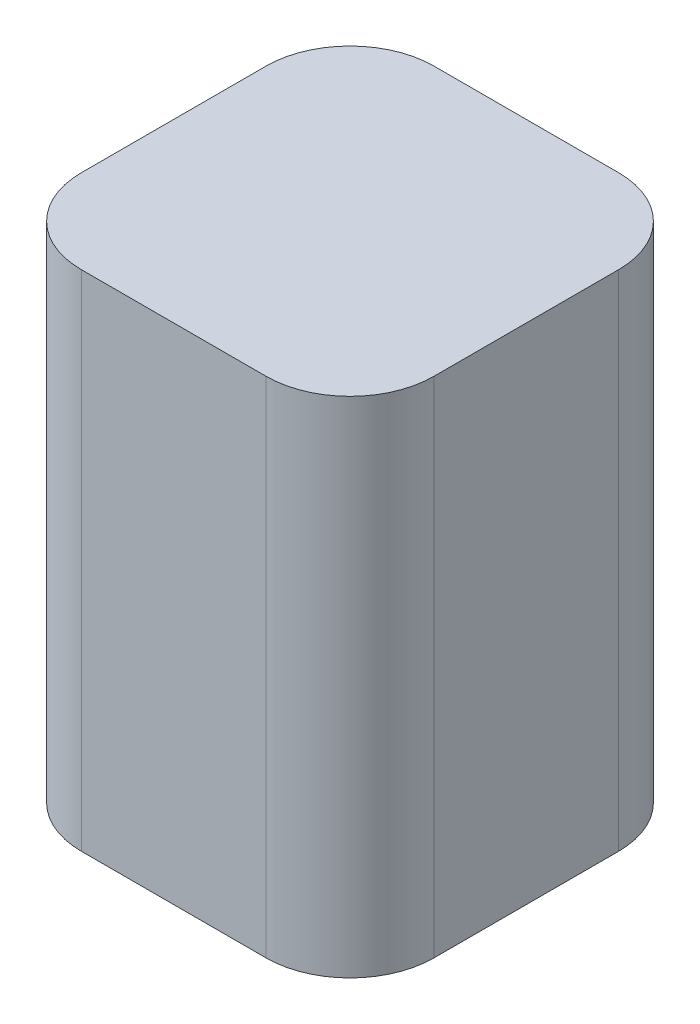
SolidWorks part; units mm, degrees
ref_plane "Front Plane" through (0, 0, 0) normal (0, 0, 1) x (1, 0, 0)
ref_plane "Top Plane" through (0, 0, 0) normal (0, 1, 0) x (1, 0, 0)
ref_plane "Right Plane" through (0, 0, 0) normal (1, 0, 0) x (0, 0, -1)
sketch "Sketch1" plane through (0, 0, 0) normal (0, 1, 0) x (1, 0, 0)
  line L1 (-21, 21) -> (21, 21)
  line L2 (-21, 21) -> (-21, -21)
  line L3 (-21, -21) -> (21, -21)
  line L4 (21, 21) -> (21, -21)
  line L5 (-21, 21) -> (21, -21) construction
  line L6 (-21, -21) -> (21, 21) construction
  point P0 (0, 0)
  dimension "D1" = 42
  dimension "D2" = 42
extrude "Boss-Extrude1" add sketch "Sketch1" along normal blind 60
fillet "Fillet1" radius 10 4 edges at (-21, 30, -21) (-21, 30, 21) (21, 30, -21) (21, 30, 21)
